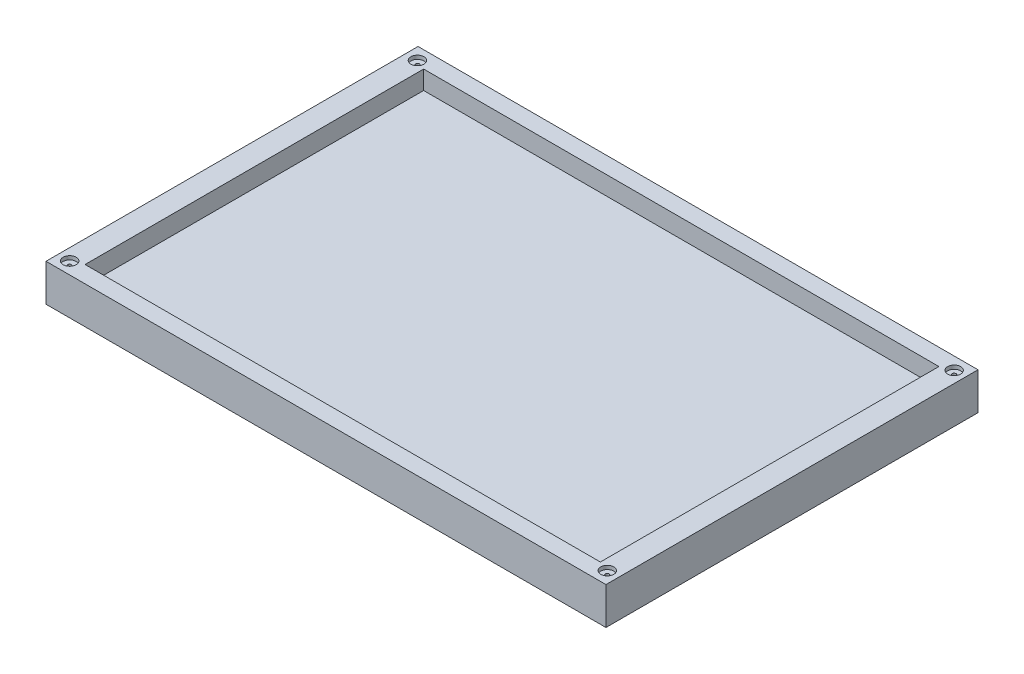
SolidWorks part; units mm, degrees
ref_plane "Front Plane" through (0, 0, 0) normal (0, 0, 1) x (1, 0, 0)
ref_plane "Top Plane" through (0, 0, 0) normal (0, 1, 0) x (1, 0, 0)
ref_plane "Right Plane" through (0, 0, 0) normal (1, 0, 0) x (0, 0, -1)
sketch "Sketch1" plane through (0, 0, 0) normal (0, 1, 0) x (1, 0, 0)
  line L1 (0, 0) -> (150.5, 0)
  line L2 (0, 0) -> (0, 100)
  line L3 (0, 100) -> (150.5, 100)
  line L4 (150.5, 0) -> (150.5, 100)
  dimension "D1" = 150.5
  dimension "D2" = 100
extrude "Boss-Extrude1" add sketch "Sketch1" along normal mid plane 10
sketch "Sketch2" plane through (0, 5, 0) normal (0, 1, 0) x (1, 0, 0)
  line L0 (0, 100) -> (0, 0) construction
  line L1 (6, 95.5) -> (144.5, 95.5)
  line L2 (6, 95.5) -> (6, 4.5)
  line L3 (6, 4.5) -> (144.5, 4.5)
  line L4 (144.5, 95.5) -> (144.5, 4.5)
  line L5 (150.5, 100) -> (0, 100) construction
  line L6 (150.5, 0) -> (150.5, 100) construction
  line L7 (0, 0) -> (150.5, 0) construction
  dimension "D1" = 6
  dimension "D2" = 4.5
  dimension "D3" = 6
  dimension "D4" = 4.5
extrude "Cut-Extrude1" cut sketch "Sketch2" against normal blind 5
sketch "Sketch3" plane through (0, 5, 0) normal (0, 1, 0) x (1, 0, 0)
  circle A0 centre (3.1591, 96.6621) radius 1.75
  circle A1 centre (3.1028, 3.2545) radius 1.75
  circle A2 centre (147.4306, 3.4369) radius 1.75
  circle A3 centre (147.4306, 96.6621) radius 1.75
  point P6 (147.4306, 4.5)
  point P9 (147.4306, 96.6621)
  point P10 (0, 0)
  dimension "D1" = 3.5
extrude "Cut-Extrude2" cut sketch "Sketch3" against normal blind 1
sketch "Sketch4" plane through (0, 4, 0) normal (0, 1, 0) x (1, 0, 0)
  circle A0 centre (3.2125, 96.6472) radius 0.5
  circle A1 centre (3.1758, 3.1285) radius 0.5
  circle A2 centre (147.4234, 3.4386) radius 0.5
  circle A3 centre (147.4306, 96.6621) radius 0.5
  dimension "D1" = 1
  dimension "D2" = 1
  dimension "D3" = 1
  dimension "D4" = 1
extrude "Cut-Extrude3" cut sketch "Sketch4" against normal blind 5
